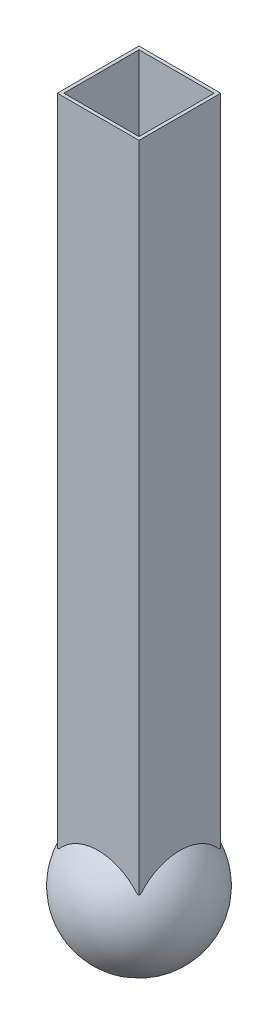
SolidWorks part; units mm, degrees
material "1060 Alloy"
ref_plane "Front Plane" through (0, 0, 0) normal (0, 0, 1) x (1, 0, 0)
ref_plane "Top Plane" through (0, 0, 0) normal (0, 1, 0) x (1, 0, 0)
ref_plane "Right Plane" through (0, 0, 0) normal (1, 0, 0) x (0, 0, -1)
sketch "Sketch1" plane through (0, 0, 0) normal (0, 1, 0) x (1, 0, 0)
  line L0 (-11.5, -11.5) -> (11.5, -11.5)
  line L1 (-12.5, 12.5) -> (12.5, 12.5)
  line L2 (-12.5, 12.5) -> (-12.5, -12.5)
  line L3 (-12.5, -12.5) -> (12.5, -12.5)
  line L4 (12.5, 12.5) -> (12.5, -12.5)
  line L5 (-12.5, 12.5) -> (12.5, -12.5) construction
  line L6 (-12.5, -12.5) -> (12.5, 12.5) construction
  line L7 (11.5, 11.5) -> (11.5, -11.5)
  line L8 (-11.5, 11.5) -> (11.5, 11.5)
  line L9 (-11.5, 11.5) -> (-11.5, -11.5)
  point P0 (0, 0)
  dimension "D1" = 25
  dimension "D2" = 25
  dimension "D3" = 1
extrude "Boss-Extrude1" add sketch "Sketch1" along normal blind 200
ref_plane "Plane1" through (0, -10, 0) normal (0, -1, 0) x (-1, 0, 0)
sketch "Sketch2" plane through (0, -10, 0) normal (0, -1, 0) x (-1, 0, 0)
  line L0 (0, 20) -> (0, -20) construction
  arc A2 (0, -20) -> (0, 20) centre (0, 0) cw
  arc A3 (0, -19) -> (0, 19) centre (0, 0) cw
revolve "Revolve1" add sketch "Sketch2" angle 360 about L0
